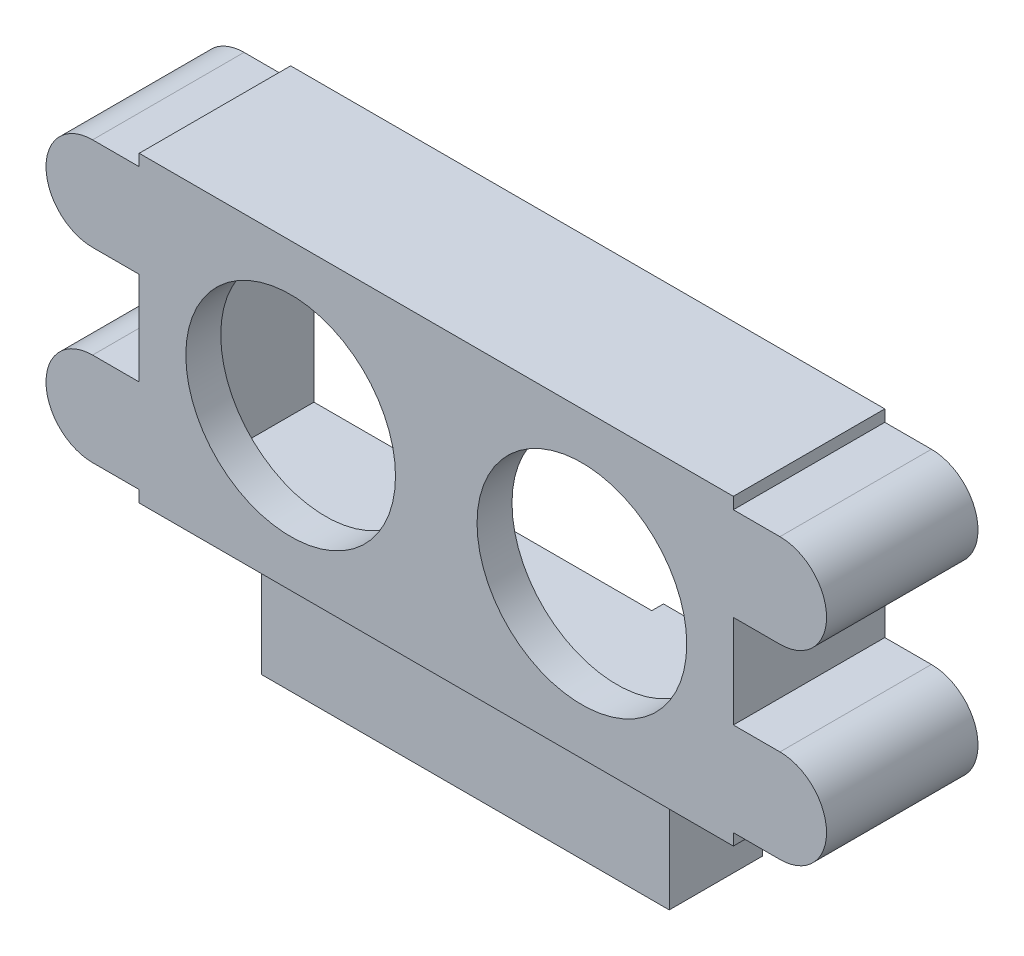
SolidWorks part; units mm, degrees
ref_plane "Ebene vorne" through (0, 0, 0) normal (0, 0, 1) x (1, 0, 0)
ref_plane "Ebene oben" through (0, 0, 0) normal (0, 1, 0) x (1, 0, 0)
ref_plane "Ebene rechts" through (0, 0, 0) normal (1, 0, 0) x (0, 0, -1)
sketch "Skizze1" plane through (0, 0, 0) normal (0, 0, 1) x (1, 0, 0)
  line L10 (549.7525, 211.3432) -> (502.7525, 211.3432)
  line L11 (502.7525, 211.3432) -> (502.7525, 189.3432)
  line L12 (502.7525, 189.3432) -> (549.7525, 189.3432)
  line L13 (549.7525, 189.3432) -> (549.7525, 211.3432)
  line L18 (551.7525, 187.3432) -> (551.7525, 213.3432)
  line L19 (500.7525, 187.3432) -> (551.7525, 187.3432)
  line L20 (500.7525, 213.3432) -> (500.7525, 187.3432)
  line L21 (551.7525, 213.3432) -> (500.7525, 213.3432)
  circle A3 centre (513.7525, 200.3432) radius 9
  circle A6 centre (538.7525, 200.3432) radius 9
  dimension "D4" = 2
extrude "Aufsatz-Linear austragen1" add sketch "Skizze1" along normal blind 3 contours A3 | A6 | L21 L20 L19 L18
sketch "Skizze3" plane through (0, 0, 0) normal (0, 0, -1) x (-1, 0, 0)
  line L4 (-551.7525, 213.3432) -> (-500.7525, 213.3432) construction
  line L5 (-551.7525, 213.3432) -> (-500.7525, 213.3432)
  line L6 (-551.7525, 187.3432) -> (-551.7525, 213.3432) construction
  line L7 (-551.7525, 187.3432) -> (-551.7525, 213.3432)
  line L8 (-549.7525, 211.3432) -> (-549.7525, 189.3432)
  line L9 (-549.7525, 189.3432) -> (-502.7525, 189.3432)
  line L10 (-502.7525, 189.3432) -> (-502.7525, 211.3432)
  line L11 (-502.7525, 211.3432) -> (-549.7525, 211.3432)
  line L12 (-549.7525, 211.3432) -> (-549.7525, 189.3432)
  line L13 (-549.7525, 189.3432) -> (-502.7525, 189.3432)
  line L14 (-502.7525, 189.3432) -> (-502.7525, 211.3432)
  line L15 (-502.7525, 211.3432) -> (-549.7525, 211.3432)
  line L16 (-500.7525, 213.3432) -> (-500.7525, 187.3432) construction
  line L17 (-500.7525, 187.3432) -> (-551.7525, 187.3432) construction
  line L18 (-500.7525, 213.3432) -> (-500.7525, 187.3432)
  line L19 (-500.7525, 187.3432) -> (-551.7525, 187.3432)
  dimension "D1" = 2
extrude "Aufsatz-Linear austragen3" add sketch "Skizze3" along normal blind 10
sketch "Skizze4" plane through (0, 0, -10) normal (0, 0, -1) x (-1, 0, 0)
  line L0 (-500.7525, 213.3432) -> (-551.7525, 213.3432) construction
  line L1 (-500.7525, 187.3432) -> (-500.7525, 213.3432) construction
  line L2 (-496.7525, 212.3432) -> (-500.7525, 212.3432)
  line L3 (-500.7525, 212.3432) -> (-500.7525, 204.3432)
  line L4 (-500.7525, 204.3432) -> (-496.7525, 204.3432)
  line L7 (-551.7525, 200.3432) -> (-490.7838, 200.3432) construction
  line L8 (-551.7525, 213.3432) -> (-551.7525, 187.3432) construction
  line L9 (-526.2525, 213.3432) -> (-526.2525, 176.8009) construction
  line L10 (-500.7525, 196.3432) -> (-496.7525, 196.3432)
  line L11 (-500.7525, 188.3432) -> (-500.7525, 196.3432)
  line L12 (-496.7525, 188.3432) -> (-500.7525, 188.3432)
  line L13 (-551.7525, 188.3432) -> (-551.7525, 196.3432)
  line L14 (-555.7525, 188.3432) -> (-551.7525, 188.3432)
  line L15 (-551.7525, 196.3432) -> (-555.7525, 196.3432)
  line L16 (-551.7525, 204.3432) -> (-555.7525, 204.3432)
  line L17 (-551.7525, 212.3432) -> (-551.7525, 204.3432)
  line L18 (-555.7525, 212.3432) -> (-551.7525, 212.3432)
  arc A0 (-496.7525, 204.3432) -> (-496.7525, 212.3432) centre (-496.7525, 208.3432) ccw
  arc A1 (-496.7525, 196.3432) -> (-496.7525, 188.3432) centre (-496.7525, 192.3432) cw
  arc A2 (-555.7525, 196.3432) -> (-555.7525, 188.3432) centre (-555.7525, 192.3432) ccw
  arc A3 (-555.7525, 204.3432) -> (-555.7525, 212.3432) centre (-555.7525, 208.3432) cw
  dimension "D1" = 5
  dimension "D2" = 4
extrude "Aufsatz-Linear austragen4" add sketch "Skizze4" against normal up to surface (13 mm away) up to face at (522.7525, 200.3432, 3)
hole_wizard "Ø3.0 (3) Durchmesser Bohrung1" positions "Skizze6" profile "Skizze7" hole size "Ø3.0" standard "ISO"
sketch "Skizze6" plane through (0, 0, -10) normal (0, 0, -1) x (-1, 0, 0)
  point P1 (-555.7525, 208.3432)
  point P4 (-555.7525, 192.3432)
  point P7 (-496.7525, 208.3432)
  point P10 (-496.7525, 192.3432)
sketch "Skizze7" plane through (555.7525, 208.3432, -10) normal (1, 0, 0) x (0, 1, 0)
  line L0 (0, 0) -> (0, 8.9013)
  line L1 (0, 8.9013) -> (1.5, 8)
  line L2 (1.5, 8) -> (1.5, 0)
  line L5 (1.5, 0) -> (0, 0)
  line L10 (0, 8.9013) -> (-1.5, 8) construction
  line L11 (0, -6.35) -> (0, 107.95) construction
  dimension "Bohrerdurchmesser" = 3
  dimension "Bohrungstiefe" = 8
  dimension "Spitzenwinkel" = 118
sketch "Skizze8" plane through (0, 187.3432, 0) normal (0, -1, 0) x (1, 0, 0)
  line L0 (551.7525, -10) -> (500.7525, -10) construction
  line L1 (519.7525, -10) -> (532.7525, -10)
  line L2 (519.7525, -10) -> (519.7525, -9)
  line L3 (519.7525, -9) -> (532.7525, -9)
  line L4 (532.7525, -10) -> (532.7525, -9)
  line L5 (526.2525, 3) -> (526.2525, -17.452) construction
  line L6 (500.7525, 3) -> (551.7525, 3) construction
  dimension "D1" = 13
  dimension "D2" = 1
extrude "Schnitt-Linear austragen1" cut sketch "Skizze8" against normal up to next contours L3 L4 L1 L2
sketch "Skizze10" plane through (0, 187.3432, 0) normal (0, -1, 0) x (1, 0, 0)
  line L0 (500.7525, -3.5) -> (552.2628, -3.5) construction
  line L1 (508.7525, 0.5) -> (543.7525, 0.5)
  line L2 (508.7525, 0.5) -> (508.7525, -7.5)
  line L3 (508.7525, -7.5) -> (543.7525, -7.5)
  line L4 (543.7525, 0.5) -> (543.7525, -7.5)
  line L5 (500.7525, 3) -> (500.7525, -10) construction
  line L6 (526.2525, 3) -> (526.2525, -17.878) construction
  line L7 (500.7525, 3) -> (551.7525, 3) construction
  dimension "D1" = 35
  dimension "D2" = 8
extrude "Aufsatz-Linear austragen5" add sketch "Skizze10" along normal blind 10 contours L1 L4 L3 L2
sketch "Skizze11" plane through (0, 177.3432, 0) normal (0, -1, 0) x (1, 0, 0)
  line L0 (508.7525, -3.5) -> (549.5925, -3.5) construction
  line L1 (508.7525, 0.5) -> (508.7525, -7.5) construction
  line L2 (526.2525, 0.5) -> (526.2525, -17.4014) construction
  line L3 (508.7525, 0.5) -> (543.7525, 0.5) construction
  line L4 (516.8025, -3.5) -> (535.7025, -3.5)
  line L5 (543.7525, 0.5) -> (543.7525, -7.5) construction
  dimension "D1" = 18.9
hole_wizard "Ø1.5 (1.5) Durchmesser Bohrung1" positions "Skizze12" profile "Skizze14" hole size "Ø1.5" standard "ISO"
sketch "Skizze12" plane through (0, 177.3432, 0) normal (0, -1, 0) x (-1, 0, 0)
  point P0 (-535.7025, 3.5)
  point P3 (-516.8025, 3.5)
sketch "Skizze14" plane through (535.7025, 177.3432, -3.5) normal (1, 0, 0) x (0, 0, -1)
  line L0 (0, 0) -> (0, 8.4506)
  line L1 (0, 8.4506) -> (0.75, 8)
  line L2 (0.75, 8) -> (0.75, 0)
  line L5 (0.75, 0) -> (0, 0)
  line L10 (0, 8.4506) -> (-0.75, 8) construction
  line L11 (0, -6.35) -> (0, 107.95) construction
  dimension "Bohrerdurchmesser" = 1.5
  dimension "Bohrungstiefe" = 8
  dimension "Spitzenwinkel" = 118
